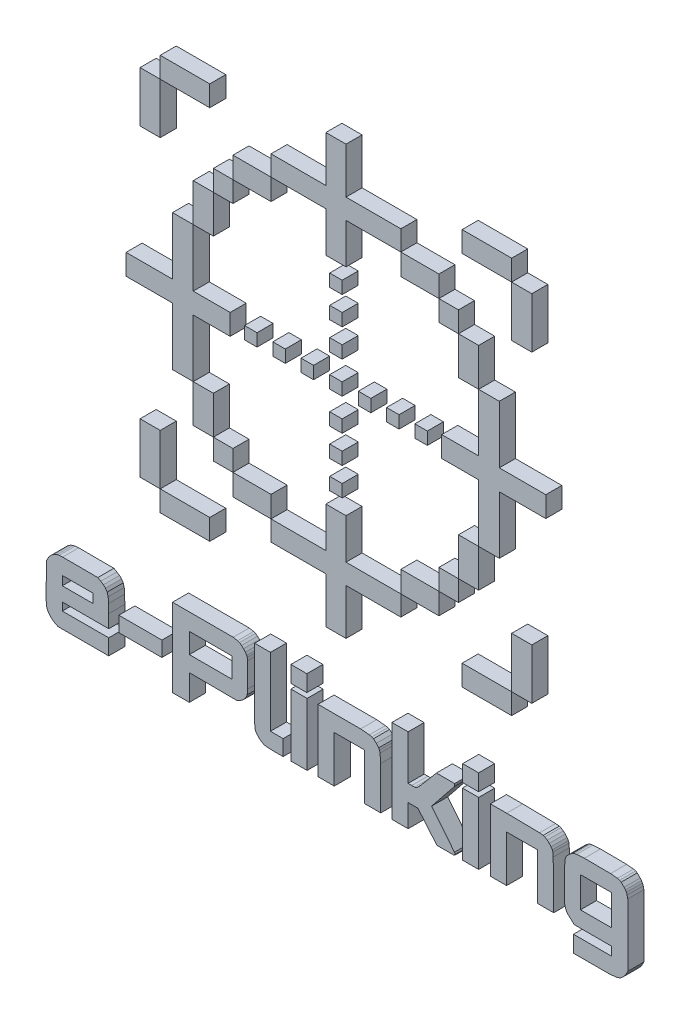
SolidWorks part; units mm, degrees
ref_plane "Plano frontal" through (0, 0, 0) normal (0, 0, 1) x (1, 0, 0)
ref_plane "Plano superior" through (0, 0, 0) normal (0, 1, 0) x (1, 0, 0)
ref_plane "Plano direito" through (0, 0, 0) normal (1, 0, 0) x (0, 0, -1)
sketch "Versão reduzida" plane through (0, 0, 0) normal (0, 0, 1) x (1, 0, 0)
  line L4 (5.1995, 6.5556) -> (5.7942, 6.5556)
  line L9 (5.1995, 6.5556) -> (5.1995, 6.307)
  line L10 (5.1995, 6.307) -> (5.7942, 6.307)
  line L11 (5.7942, 6.5556) -> (5.7942, 6.307)
  line L24 (0.9429, 4.1766) -> (6.3179, 4.1766) construction
  line L25 (5.7942, 6.307) -> (6.0362, 6.307)
  line L26 (5.7942, 6.307) -> (5.7942, 5.6987)
  line L28 (5.7942, 5.6987) -> (6.0362, 5.6987)
  line L29 (6.0362, 6.307) -> (6.0362, 5.6987)
  line L31 (3.805, 6.1961) -> (4.4636, 6.1961)
  line L33 (3.805, 5.9541) -> (4.4636, 5.9541)
  line L34 (4.4636, 6.1961) -> (4.4636, 5.9541)
  line L35 (4.4636, 5.9541) -> (4.9206, 5.9541)
  line L36 (4.4636, 5.9541) -> (4.4636, 5.6987)
  line L52 (4.4636, 5.6987) -> (4.9206, 5.6987)
  line L53 (4.9206, 5.9541) -> (4.9206, 5.6987)
  line L55 (4.9206, 5.6987) -> (5.1558, 5.6987)
  line L56 (4.9206, 5.6987) -> (4.9206, 5.4501)
  line L58 (4.9206, 5.4501) -> (5.1558, 5.4501)
  line L59 (5.1558, 5.6987) -> (5.1558, 5.4501)
  line L61 (5.1558, 5.4501) -> (5.3977, 5.4501)
  line L62 (5.1558, 5.4501) -> (5.1558, 4.9934)
  line L63 (5.1558, 4.9934) -> (5.3977, 4.9934)
  line L64 (5.3977, 5.4501) -> (5.3977, 4.9934)
  line L65 (5.3977, 4.9934) -> (5.6464, 4.9934)
  line L66 (5.3977, 4.9934) -> (5.3977, 4.3009)
  line L67 (5.6464, 4.9934) -> (5.6464, 4.3009)
  line L68 (4.9542, 4.3009) -> (5.3977, 4.3009)
  line L69 (4.9542, 4.3009) -> (4.9542, 4.0522)
  line L71 (6.2042, 4.3009) -> (6.2042, 4.0522)
  line L72 (3.805, 6.1961) -> (3.805, 6.7471)
  line L73 (3.805, 6.7471) -> (3.5631, 6.7471)
  line L82 (3.805, 5.9541) -> (3.805, 5.4703)
  line L85 (3.805, 5.4703) -> (3.5631, 5.4703)
  line L87 (4.2922, 4.2516) -> (4.4422, 4.2516)
  line L88 (4.6316, 4.2516) -> (4.7816, 4.2516)
  line L89 (3.805, 2.1571) -> (3.805, 1.606)
  line L90 (5.6464, 4.3009) -> (6.2042, 4.3009)
  line L91 (3.759, 5.309) -> (3.609, 5.309)
  line L92 (3.759, 5.309) -> (3.759, 5.159)
  line L105 (3.759, 5.159) -> (3.609, 5.159)
  line L106 (3.759, 4.9729) -> (3.609, 4.9729)
  line L107 (3.759, 4.9729) -> (3.759, 4.8229)
  line L108 (3.759, 4.8229) -> (3.609, 4.8229)
  line L125 (3.759, 4.6369) -> (3.609, 4.6369)
  line L126 (3.759, 4.6369) -> (3.759, 4.4869)
  line L127 (3.759, 4.4869) -> (3.609, 4.4869)
  line L128 (3.759, 4.2516) -> (3.609, 4.2516)
  line L141 (3.759, 4.2516) -> (3.759, 4.1016)
  line L142 (3.9529, 4.2516) -> (4.1029, 4.2516)
  line L143 (3.9529, 4.2516) -> (3.9529, 4.1016)
  line L160 (4.1029, 4.2516) -> (4.1029, 4.1016)
  line L161 (4.2922, 4.2516) -> (4.4422, 4.2516)
  line L166 (4.6316, 4.2516) -> (4.7816, 4.2516)
  line L169 (4.9542, 4.3009) -> (5.3977, 4.3009)
  line L173 (4.9542, 4.3009) -> (4.9542, 4.0522)
  line L177 (6.2042, 4.3009) -> (6.2042, 4.0522)
  line L183 (5.6464, 4.3009) -> (6.2042, 4.3009)
  line L184 (3.5631, 5.4703) -> (3.5631, 5.9541)
  line L185 (3.805, 5.4703) -> (3.5631, 5.4703)
  line L186 (3.805, 5.4703) -> (3.805, 5.9541)
  line L188 (3.805, 6.7471) -> (3.5631, 6.7471)
  line L189 (1.7217, 4.3009) -> (1.1639, 4.3009)
  line L191 (1.1639, 4.3009) -> (1.1639, 4.0522)
  line L192 (4.6316, 4.2516) -> (4.6316, 4.1016)
  line L193 (2.4139, 4.3009) -> (2.4139, 4.0522)
  line L206 (2.4139, 4.3009) -> (1.9703, 4.3009)
  line L207 (2.5865, 4.2516) -> (2.5865, 4.1016)
  line L208 (4.7816, 4.2516) -> (4.7816, 4.1016)
  line L209 (2.7365, 4.2516) -> (2.7365, 4.1016)
  line L219 (2.7365, 4.2516) -> (2.5865, 4.2516)
  line L220 (2.9258, 4.2516) -> (2.9258, 4.1016)
  line L347 (3.684, 3.7162) -> (3.684, 3.5302) construction
  line L409 (3.0758, 4.2516) -> (3.0758, 4.1016)
  line L410 (3.0758, 4.2516) -> (2.9258, 4.2516)
  line L411 (3.2652, 4.2516) -> (3.2652, 4.1016)
  line L412 (3.4152, 4.2516) -> (3.4152, 4.1016)
  line L413 (3.4152, 4.2516) -> (3.2652, 4.2516)
  line L414 (3.609, 4.2516) -> (3.609, 4.1016)
  line L415 (3.609, 4.6369) -> (3.609, 4.4869)
  line L416 (3.609, 4.9729) -> (3.609, 4.8229)
  line L417 (3.609, 5.309) -> (3.609, 5.159)
  line L418 (1.7217, 4.3009) -> (1.1639, 4.3009)
  line L419 (2.7365, 4.2516) -> (2.5865, 4.2516)
  line L420 (3.0758, 4.2516) -> (2.9258, 4.2516)
  line L421 (3.5631, 5.9541) -> (3.5631, 5.4703)
  line L422 (3.5631, 6.1961) -> (3.5631, 6.7471)
  line L423 (1.1639, 4.3009) -> (1.1639, 4.0522)
  line L424 (2.4139, 4.3009) -> (2.4139, 4.0522)
  line L425 (2.4139, 4.3009) -> (1.9703, 4.3009)
  line L426 (1.7217, 4.9934) -> (1.7217, 4.3009)
  line L427 (1.9703, 4.9934) -> (1.9703, 4.3009)
  line L428 (1.9703, 4.9934) -> (1.7217, 4.9934)
  line L429 (1.9703, 5.4501) -> (1.9703, 4.9934)
  line L430 (2.2123, 4.9934) -> (1.9703, 4.9934)
  line L431 (2.2123, 5.4501) -> (2.2123, 4.9934)
  line L432 (2.2123, 5.4501) -> (1.9703, 5.4501)
  line L433 (2.2123, 5.6987) -> (2.2123, 5.4501)
  line L434 (2.4475, 5.4501) -> (2.2123, 5.4501)
  line L435 (2.4475, 5.6987) -> (2.4475, 5.4501)
  line L436 (2.4475, 5.6987) -> (2.2123, 5.6987)
  line L437 (2.4475, 5.9541) -> (2.4475, 5.6987)
  line L438 (2.9045, 5.6987) -> (2.4475, 5.6987)
  line L439 (2.9045, 5.9541) -> (2.9045, 5.6987)
  line L440 (2.9045, 5.9541) -> (2.4475, 5.9541)
  line L441 (2.9045, 6.1961) -> (2.9045, 5.9541)
  line L442 (3.5631, 5.9541) -> (2.9045, 5.9541)
  line L443 (3.684, 1.606) -> (3.684, 1.4107) construction
  line L444 (3.5631, 6.1961) -> (2.9045, 6.1961)
  line L445 (1.3319, 6.307) -> (1.3319, 5.6987)
  line L446 (1.5738, 5.6987) -> (1.3319, 5.6987)
  line L447 (1.5738, 6.307) -> (1.5738, 5.6987)
  line L448 (1.5738, 6.307) -> (1.3319, 6.307)
  line L449 (1.5738, 6.5556) -> (1.5738, 6.307)
  line L450 (2.1686, 6.307) -> (1.5738, 6.307)
  line L451 (2.1686, 6.5556) -> (2.1686, 6.307)
  line L452 (2.1686, 6.5556) -> (1.5738, 6.5556)
  line L453 (2.1686, 1.7975) -> (1.5738, 1.7975)
  line L454 (2.1686, 1.7975) -> (2.1686, 2.0462)
  line L455 (2.1686, 2.0462) -> (1.5738, 2.0462)
  line L456 (1.5738, 1.7975) -> (1.5738, 2.0462)
  line L457 (1.5738, 2.0462) -> (1.3319, 2.0462)
  line L458 (1.5738, 2.0462) -> (1.5738, 2.6544)
  line L459 (1.5738, 2.6544) -> (1.3319, 2.6544)
  line L460 (1.3319, 2.0462) -> (1.3319, 2.6544)
  line L461 (3.5631, 2.1571) -> (2.9045, 2.1571)
  line L462 (3.684, 5.159) -> (3.684, 4.9729) construction
  line L463 (3.5631, 2.399) -> (2.9045, 2.399)
  line L464 (2.9045, 2.1571) -> (2.9045, 2.399)
  line L465 (2.9045, 2.399) -> (2.4475, 2.399)
  line L466 (2.9045, 2.399) -> (2.9045, 2.6544)
  line L467 (2.9045, 2.6544) -> (2.4475, 2.6544)
  line L468 (2.4475, 2.399) -> (2.4475, 2.6544)
  line L469 (2.4475, 2.6544) -> (2.2123, 2.6544)
  line L470 (2.4475, 2.6544) -> (2.4475, 2.9031)
  line L471 (2.4475, 2.9031) -> (2.2123, 2.9031)
  line L472 (2.2123, 2.6544) -> (2.2123, 2.9031)
  line L473 (2.2123, 2.9031) -> (1.9703, 2.9031)
  line L474 (2.2123, 2.9031) -> (2.2123, 3.3597)
  line L475 (2.2123, 3.3597) -> (1.9703, 3.3597)
  line L476 (1.9703, 2.9031) -> (1.9703, 3.3597)
  line L477 (1.9703, 3.3597) -> (1.7217, 3.3597)
  line L478 (1.9703, 3.3597) -> (1.9703, 4.0522)
  line L479 (1.7217, 3.3597) -> (1.7217, 4.0522)
  line L480 (2.4139, 4.0522) -> (1.9703, 4.0522)
  line L481 (3.5631, 2.1571) -> (3.5631, 1.606)
  line L482 (3.5631, 2.399) -> (3.5631, 2.8829)
  line L483 (3.0758, 4.1016) -> (2.9258, 4.1016)
  line L484 (2.7365, 4.1016) -> (2.5865, 4.1016)
  line L485 (1.7217, 4.0522) -> (1.1639, 4.0522)
  line L486 (3.609, 3.0442) -> (3.609, 3.1942)
  line L487 (3.609, 3.3802) -> (3.609, 3.5302)
  line L488 (3.609, 3.7162) -> (3.609, 3.8662)
  line L489 (3.4152, 4.1016) -> (3.2652, 4.1016)
  line L490 (3.0758, 4.1016) -> (2.9258, 4.1016)
  line L491 (2.7365, 4.1016) -> (2.5865, 4.1016)
  line L492 (2.4139, 4.0522) -> (1.9703, 4.0522)
  line L493 (1.7217, 4.0522) -> (1.1639, 4.0522)
  line L494 (3.5631, 2.1571) -> (3.5631, 1.606)
  line L495 (3.805, 1.606) -> (3.5631, 1.606)
  line L496 (3.805, 2.8829) -> (3.805, 2.399)
  line L497 (3.805, 2.8829) -> (3.5631, 2.8829)
  line L498 (3.5631, 2.8829) -> (3.5631, 2.399)
  line L499 (5.6464, 4.0522) -> (6.2042, 4.0522)
  line L500 (4.9542, 4.0522) -> (5.3977, 4.0522)
  line L501 (4.6316, 4.1016) -> (4.7816, 4.1016)
  line L502 (4.2922, 4.1016) -> (4.4422, 4.1016)
  line L503 (3.9529, 4.1016) -> (4.1029, 4.1016)
  line L504 (3.759, 4.1016) -> (3.609, 4.1016)
  line L505 (3.684, 3.3802) -> (3.684, 3.1942) construction
  line L506 (3.759, 3.8662) -> (3.609, 3.8662)
  line L507 (3.759, 3.7162) -> (3.759, 3.8662)
  line L508 (3.759, 3.7162) -> (3.609, 3.7162)
  line L509 (3.684, 3.0442) -> (3.684, 2.8829) construction
  line L510 (3.759, 3.5302) -> (3.609, 3.5302)
  line L511 (3.759, 3.3802) -> (3.759, 3.5302)
  line L512 (3.759, 3.3802) -> (3.609, 3.3802)
  line L513 (4.2922, 4.2516) -> (4.2922, 4.1016)
  line L514 (3.759, 3.1942) -> (3.609, 3.1942)
  line L515 (3.759, 3.0442) -> (3.759, 3.1942)
  line L516 (3.759, 3.0442) -> (3.609, 3.0442)
  line L517 (5.6464, 4.0522) -> (6.2042, 4.0522)
  line L518 (4.6316, 4.1016) -> (4.7816, 4.1016)
  line L519 (4.2922, 4.1016) -> (4.4422, 4.1016)
  line L520 (3.805, 2.8829) -> (3.5631, 2.8829)
  line L521 (3.805, 2.399) -> (3.805, 2.8829)
  line L522 (3.684, 4.8229) -> (3.684, 4.6369) construction
  line L523 (3.805, 1.606) -> (3.5631, 1.606)
  line L524 (3.805, 2.1571) -> (3.805, 1.606)
  line L525 (3.684, 4.4869) -> (3.684, 4.2516) construction
  line L526 (4.9542, 4.0522) -> (5.3977, 4.0522)
  line L527 (5.6464, 3.3597) -> (5.6464, 4.0522)
  line L528 (5.3977, 3.3597) -> (5.3977, 4.0522)
  line L529 (5.3977, 3.3597) -> (5.6464, 3.3597)
  line L530 (5.3977, 2.9031) -> (5.3977, 3.3597)
  line L531 (5.1558, 3.3597) -> (5.3977, 3.3597)
  line L532 (5.1558, 2.9031) -> (5.1558, 3.3597)
  line L533 (5.1558, 2.9031) -> (5.3977, 2.9031)
  line L534 (5.1558, 2.6544) -> (5.1558, 2.9031)
  line L535 (4.9206, 2.9031) -> (5.1558, 2.9031)
  line L536 (4.9206, 2.6544) -> (4.9206, 2.9031)
  line L537 (4.9206, 2.6544) -> (5.1558, 2.6544)
  line L538 (4.9206, 2.399) -> (4.9206, 2.6544)
  line L539 (4.4636, 2.6544) -> (4.9206, 2.6544)
  line L540 (4.4636, 2.399) -> (4.4636, 2.6544)
  line L541 (4.4636, 2.399) -> (4.9206, 2.399)
  line L542 (4.4636, 2.1571) -> (4.4636, 2.399)
  line L543 (3.805, 2.399) -> (4.4636, 2.399)
  line L544 (3.684, 4.1016) -> (3.684, 3.8662) construction
  line L545 (3.805, 2.1571) -> (4.4636, 2.1571)
  line L546 (6.0362, 2.0462) -> (6.0362, 2.6544)
  line L547 (5.7942, 2.6544) -> (6.0362, 2.6544)
  line L548 (5.7942, 2.0462) -> (5.7942, 2.6544)
  line L549 (5.7942, 2.0462) -> (6.0362, 2.0462)
  line L550 (5.7942, 1.7975) -> (5.7942, 2.0462)
  line L551 (5.1995, 2.0462) -> (5.7942, 2.0462)
  line L552 (5.1995, 1.7975) -> (5.1995, 2.0462)
  line L553 (5.1995, 1.7975) -> (5.7942, 1.7975)
  line L554 (3.5631, 6.1961) -> (3.5631, 6.7471)
  line L555 (3.684, 5.4703) -> (3.684, 5.309) construction
  line L556 (4.4422, 4.2516) -> (4.4422, 4.1016)
  line L557 (3.805, 6.1961) -> (3.805, 6.7471)
  line L558 (0.4024, 0.7509) -> (0.8245, 0.7492)
  line L559 (0.8245, 0.7492) -> (0.8605, 0.7292)
  line L560 (0.8605, 0.7292) -> (0.8917, 0.7082)
  line L561 (0.8917, 0.7082) -> (0.9161, 0.6856)
  line L562 (0.9161, 0.6856) -> (0.9368, 0.6539)
  line L563 (0.9368, 0.6539) -> (0.9487, 0.6117)
  line L564 (0.9487, 0.6117) -> (0.9542, 0.5447)
  line L565 (0.9542, 0.5447) -> (0.9555, 0.4388)
  line L566 (0.9555, 0.4388) -> (0.9555, 0.2821)
  line L567 (0.9555, 0.2821) -> (0.3978, 0.2821)
  line L568 (0.3978, 0.2821) -> (0.3978, 0.1872)
  line L569 (0.3978, 0.1872) -> (0.9555, 0.188)
  line L570 (0.9555, 0.188) -> (0.9555, -0.0002)
  line L571 (0.9555, -0.0002) -> (0.3473, 0)
  line L572 (0.3473, 0) -> (0.3135, 0.0157)
  line L573 (0.3135, 0.0157) -> (0.2806, 0.0362)
  line L574 (0.2806, 0.0362) -> (0.2511, 0.0644)
  line L575 (0.2511, 0.0644) -> (0.2275, 0.0972)
  line L576 (0.2275, 0.0972) -> (0.2124, 0.1318)
  line L577 (0.2124, 0.1318) -> (0.2072, 0.1586)
  line L578 (0.2072, 0.1586) -> (0.2044, 0.2027)
  line L579 (0.2044, 0.2027) -> (0.2062, 0.6148)
  line L580 (0.2062, 0.6148) -> (0.2244, 0.6493)
  line L581 (0.2244, 0.6493) -> (0.2449, 0.6804)
  line L582 (0.2449, 0.6804) -> (0.2706, 0.7069)
  line L583 (0.2706, 0.7069) -> (0.3004, 0.7277)
  line L584 (0.3004, 0.7277) -> (0.3346, 0.7423)
  line L585 (0.3346, 0.7423) -> (0.3597, 0.7478)
  line L586 (0.3597, 0.7478) -> (0.4024, 0.7509)
  line L587 (1.7217, 0.0002) -> (1.7217, 0.9411)
  line L588 (0.3978, 0.5576) -> (0.7674, 0.5576)
  line L589 (0.3978, 0.5576) -> (0.3978, 0.4501)
  line L590 (0.3978, 0.4501) -> (0.7674, 0.4501)
  line L591 (0.7674, 0.5576) -> (0.7674, 0.4501)
  line L592 (1.0765, 0.4837) -> (1.594, 0.4837)
  line L593 (1.0765, 0.4837) -> (1.0765, 0.3023)
  line L594 (1.0765, 0.3023) -> (1.594, 0.3023)
  line L595 (1.594, 0.4837) -> (1.594, 0.3023)
  line L596 (1.9233, 0.7391) -> (2.434, 0.7391)
  line L597 (1.9233, 0.7391) -> (1.9233, 0.4971)
  line L598 (1.9233, 0.4971) -> (2.434, 0.4971)
  line L599 (2.434, 0.7391) -> (2.434, 0.4971)
  line L600 (3.143, 1.0045) -> (3.3349, 1.0045)
  line L601 (3.143, 1.0045) -> (3.143, 0.8075)
  line L602 (3.143, 0.8075) -> (3.3349, 0.8075)
  line L603 (3.3349, 1.0045) -> (3.3349, 0.8075)
  line L604 (5.2062, 1.0045) -> (5.3977, 1.0045)
  line L605 (5.2062, 1.0045) -> (5.2062, 0.8075)
  line L606 (5.2062, 0.8075) -> (5.3977, 0.8075)
  line L607 (5.3977, 1.0045) -> (5.3977, 0.8075)
  line L608 (6.6209, 0.5576) -> (6.9938, 0.5576)
  line L609 (6.6209, 0.5576) -> (6.6209, 0.1914)
  line L610 (6.6209, 0.1914) -> (6.9938, 0.1914)
  line L611 (6.9938, 0.5576) -> (6.9938, 0.1914)
  line L612 (1.7217, 0.9411) -> (2.4504, 0.9411)
  line L613 (2.4504, 0.9411) -> (2.5026, 0.9311)
  line L614 (2.5026, 0.9311) -> (2.5248, 0.9228)
  line L615 (2.5248, 0.9228) -> (2.5496, 0.9061)
  line L616 (2.5496, 0.9061) -> (2.5743, 0.8838)
  line L617 (2.5743, 0.8838) -> (2.5964, 0.8586)
  line L618 (2.5964, 0.8586) -> (2.6131, 0.8332)
  line L619 (2.6131, 0.8332) -> (2.6198, 0.8152)
  line L620 (2.6198, 0.8152) -> (2.6238, 0.7845)
  line L621 (2.6238, 0.7845) -> (2.6218, 0.4873)
  line L622 (2.6218, 0.4873) -> (2.6186, 0.4266)
  line L623 (2.6186, 0.4266) -> (2.6055, 0.3949)
  line L624 (2.6055, 0.3949) -> (2.5876, 0.3682)
  line L625 (2.5876, 0.3682) -> (2.564, 0.3454)
  line L626 (2.564, 0.3454) -> (2.5339, 0.3255)
  line L627 (2.5339, 0.3255) -> (2.4979, 0.3056)
  line L628 (2.4979, 0.3056) -> (1.9233, 0.3095)
  line L629 (1.9233, 0.3095) -> (1.9233, 0.0002)
  line L630 (1.9233, 0.0002) -> (1.7217, 0.0002)
  line L631 (2.7082, 1.0079) -> (2.8977, 1.0079)
  line L632 (2.8977, 1.0079) -> (2.8977, 0.1869)
  line L633 (2.8977, 0.1869) -> (3.0504, 0.1871)
  line L634 (3.0504, 0.1871) -> (3.0504, -0.0002)
  line L635 (3.0504, -0.0002) -> (2.9204, -0.0003)
  line L636 (2.9204, -0.0003) -> (2.8557, 0.0024)
  line L637 (2.8557, 0.0024) -> (2.8317, 0.0062)
  line L638 (2.8317, 0.0062) -> (2.8137, 0.0125)
  line L639 (2.8137, 0.0125) -> (2.786, 0.0281)
  line L640 (2.786, 0.0281) -> (2.7602, 0.0485)
  line L641 (2.7602, 0.0485) -> (2.738, 0.0719)
  line L642 (2.738, 0.0719) -> (2.7213, 0.0966)
  line L643 (2.7213, 0.0966) -> (2.7128, 0.1197)
  line L644 (2.7128, 0.1197) -> (2.7082, 0.1766)
  line L645 (2.7082, 0.1766) -> (2.7082, 1.0079)
  line L646 (3.6639, 0.5576) -> (4.0268, 0.5576)
  line L647 (3.143, 0.7492) -> (3.3379, 0.7492)
  line L648 (3.143, 0.7492) -> (3.143, -0.0002)
  line L649 (3.143, -0.0002) -> (3.3379, -0.0002)
  line L650 (3.3379, 0.7492) -> (3.3379, -0.0002)
  line L651 (3.469, 0.753) -> (3.6639, 0.753)
  line L652 (3.469, 0.753) -> (3.469, -0.0002)
  line L653 (3.469, -0.0002) -> (3.6639, -0.0002)
  line L654 (3.6639, 0.5576) -> (3.6639, -0.0002)
  line L655 (4.0268, 0.5576) -> (4.0268, -0.0002)
  line L656 (4.0268, -0.0002) -> (4.2222, -0.0002)
  line L657 (4.2222, -0.0002) -> (4.2222, 0.5147)
  line L658 (4.2222, 0.5147) -> (4.2132, 0.618)
  line L659 (4.2132, 0.618) -> (4.2073, 0.6461)
  line L660 (4.2073, 0.6461) -> (4.1985, 0.6653)
  line L661 (4.1985, 0.6653) -> (4.169, 0.6977)
  line L662 (4.169, 0.6977) -> (4.1349, 0.7281)
  line L663 (4.1349, 0.7281) -> (4.1145, 0.7373)
  line L664 (4.1145, 0.7373) -> (4.0853, 0.7434)
  line L665 (4.0853, 0.7434) -> (3.9803, 0.753)
  line L666 (3.9803, 0.753) -> (3.6639, 0.753)
  line L667 (4.551, 0.4717) -> (4.595, 0.4717)
  line L668 (4.3561, 1.0079) -> (4.551, 1.0079)
  line L669 (4.3561, 1.0079) -> (4.3561, -0.0002)
  line L670 (4.3561, -0.0002) -> (4.551, -0.0002)
  line L671 (4.551, 1.0079) -> (4.551, 0.4717)
  line L672 (4.595, 0.4717) -> (4.6283, 0.472)
  line L673 (4.6283, 0.472) -> (4.6514, 0.4755)
  line L674 (4.6514, 0.4755) -> (4.6954, 0.519)
  line L675 (4.6954, 0.519) -> (4.8906, 0.7492)
  line L676 (4.8906, 0.7492) -> (5.1099, 0.7492)
  line L677 (5.1099, 0.7492) -> (5.1088, 0.7321)
  line L678 (5.1088, 0.7321) -> (5.1045, 0.7143)
  line L679 (5.1045, 0.7143) -> (4.8332, 0.3763)
  line L680 (4.8332, 0.3763) -> (5.1076, 0.0337)
  line L681 (5.1076, 0.0337) -> (5.1154, 0.015)
  line L682 (5.1154, 0.015) -> (5.1137, 0.0062)
  line L683 (0, 0) -> (7.4151, 0) construction
  line L684 (5.1137, 0.0062) -> (5.1008, 0)
  line L685 (6.9938, 0) -> (6.9938, -0.1043)
  line L686 (5.1008, 0) -> (4.8971, -0.0001)
  line L687 (4.8971, -0.0001) -> (4.6684, 0.272)
  line L688 (4.6684, 0.272) -> (4.551, 0.272)
  line L689 (4.551, 0.272) -> (4.551, -0.0002)
  line L690 (5.7338, 0.753) -> (6.1303, 0.7475)
  line L691 (5.2027, 0.7492) -> (5.398, 0.7492)
  line L692 (5.2027, 0.7492) -> (5.2027, -0.0002)
  line L693 (5.2027, -0.0002) -> (5.398, -0.0002)
  line L694 (5.398, 0.7492) -> (5.398, -0.0002)
  line L695 (5.5389, 0.753) -> (5.7338, 0.753)
  line L696 (5.5389, 0.753) -> (5.5389, -0.0002)
  line L697 (5.5389, -0.0002) -> (5.7338, -0.0002)
  line L698 (5.7338, 0.5576) -> (5.7338, -0.0002)
  line L699 (6.1303, 0.7475) -> (6.1739, 0.7428)
  line L700 (6.1739, 0.7428) -> (6.1923, 0.7354)
  line L701 (6.1923, 0.7354) -> (6.2214, 0.7172)
  line L702 (6.2214, 0.7172) -> (6.2459, 0.6956)
  line L703 (6.2459, 0.6956) -> (6.267, 0.6712)
  line L704 (6.267, 0.6712) -> (6.2826, 0.6462)
  line L705 (6.2826, 0.6462) -> (6.2894, 0.6243)
  line L706 (6.2894, 0.6243) -> (6.2933, 0.5769)
  line L707 (6.2933, 0.5769) -> (6.2989, -0.0002)
  line L708 (6.2989, -0.0002) -> (6.1034, -0.0002)
  line L709 (6.1034, -0.0002) -> (6.1034, 0.5576)
  line L710 (6.1034, 0.5576) -> (5.7338, 0.5576)
  line L711 (6.9938, -0.1043) -> (6.5369, -0.1043)
  line L712 (6.5369, -0.1043) -> (6.5369, -0.3019)
  line L713 (6.5369, -0.3019) -> (6.9623, -0.3019)
  line L714 (6.9623, -0.3019) -> (7.0512, -0.2937)
  line L715 (7.0512, -0.2937) -> (7.0964, -0.2797)
  line L716 (7.0964, -0.2797) -> (7.1302, -0.2526)
  line L717 (7.1302, -0.2526) -> (7.1539, -0.2261)
  line L718 (7.1539, -0.2261) -> (7.173, -0.1965)
  line L719 (7.173, -0.1965) -> (7.1887, -0.1648)
  line L720 (7.1887, -0.1648) -> (7.1887, 0.5892)
  line L721 (7.1887, 0.5892) -> (7.1811, 0.6245)
  line L722 (7.1811, 0.6245) -> (7.1725, 0.6497)
  line L723 (7.1725, 0.6497) -> (7.1605, 0.6689)
  line L724 (7.1605, 0.6689) -> (7.1444, 0.6879)
  line L725 (7.1444, 0.6879) -> (7.1094, 0.7235)
  line L726 (7.1094, 0.7235) -> (7.0904, 0.7345)
  line L727 (7.0904, 0.7345) -> (7.0654, 0.7419)
  line L728 (7.0654, 0.7419) -> (6.9816, 0.749)
  line L729 (6.9816, 0.749) -> (6.6672, 0.7514)
  line L730 (6.6672, 0.7514) -> (6.5757, 0.7461)
  line L731 (6.5757, 0.7461) -> (6.547, 0.7402)
  line L732 (6.547, 0.7402) -> (6.5251, 0.7314)
  line L733 (6.5251, 0.7314) -> (6.4882, 0.7035)
  line L734 (6.4882, 0.7035) -> (6.4547, 0.6683)
  line L735 (6.4547, 0.6683) -> (6.4443, 0.6489)
  line L736 (6.4443, 0.6489) -> (6.437, 0.6238)
  line L737 (6.437, 0.6238) -> (6.4296, 0.5428)
  line L738 (6.4296, 0.5428) -> (6.4271, 0.3981)
  line L739 (6.4271, 0.3981) -> (6.4274, 0.2263)
  line L740 (6.4274, 0.2263) -> (6.4327, 0.1445)
  line L741 (6.4327, 0.1445) -> (6.4442, 0.1086)
  line L742 (6.4442, 0.1086) -> (6.4628, 0.0752)
  line L743 (6.4628, 0.0752) -> (6.5471, 0)
  line L744 (6.5471, 0) -> (6.9938, 0)
  point P169 (3.684, 4.1766)
  point P369 (0, 0)
  point P370 (0, 0)
sketch "Frame 190 x 150" plane through (0, 0, 0) normal (0, 0, 1) x (1, 0, 0)
  line L4 (31.5113, 69.6228) -> (43.847, 69.6228)
  line L9 (31.5113, 69.6228) -> (31.5113, 64.4659)
  line L10 (31.5113, 64.4659) -> (43.847, 64.4659)
  line L11 (43.847, 69.6228) -> (43.847, 64.4659)
  line L24 (-56.7725, 20.2803) -> (54.7079, 20.2803) construction
  line L25 (43.847, 64.4659) -> (48.8648, 64.4659)
  line L26 (43.847, 64.4659) -> (43.847, 51.8512)
  line L28 (43.847, 51.8512) -> (48.8648, 51.8512)
  line L29 (48.8648, 64.4659) -> (48.8648, 51.8512)
  line L31 (2.589, 62.1656) -> (16.2488, 62.1656)
  line L33 (2.589, 57.1478) -> (16.2488, 57.1478)
  line L34 (16.2488, 62.1656) -> (16.2488, 57.1478)
  line L35 (16.2488, 57.1478) -> (25.7271, 57.1478)
  line L36 (16.2488, 57.1478) -> (16.2488, 51.8512)
  line L52 (16.2488, 51.8512) -> (25.7271, 51.8512)
  line L53 (25.7271, 57.1478) -> (25.7271, 51.8512)
  line L55 (25.7271, 51.8512) -> (30.6056, 51.8512)
  line L56 (25.7271, 51.8512) -> (25.7271, 46.6939)
  line L58 (25.7271, 46.6939) -> (30.6056, 46.6939)
  line L59 (30.6056, 51.8512) -> (30.6056, 46.6939)
  line L61 (30.6056, 46.6939) -> (35.6234, 46.6939)
  line L62 (30.6056, 46.6939) -> (30.6056, 37.2219)
  line L63 (30.6056, 37.2219) -> (35.6234, 37.2219)
  line L64 (35.6234, 46.6939) -> (35.6234, 37.2219)
  line L65 (35.6234, 37.2219) -> (40.7807, 37.2219)
  line L66 (35.6234, 37.2219) -> (35.6234, 22.8589)
  line L67 (40.7807, 37.2219) -> (40.7807, 22.8589)
  line L68 (26.4242, 22.8589) -> (35.6234, 22.8589)
  line L69 (26.4242, 22.8589) -> (26.4242, 17.7017)
  line L71 (52.3497, 22.8589) -> (52.3497, 17.7017)
  line L72 (2.589, 62.1656) -> (2.589, 73.5953)
  line L73 (2.589, 73.5953) -> (-2.4289, 73.5953)
  line L82 (2.589, 57.1478) -> (2.589, 47.1121)
  line L85 (2.589, 47.1121) -> (-2.4289, 47.1121)
  line L87 (12.6945, 21.8358) -> (15.8056, 21.8358)
  line L88 (19.7335, 21.8358) -> (22.8446, 21.8358)
  line L89 (2.589, -21.605) -> (2.589, -33.0347)
  line L90 (40.7807, 22.8589) -> (52.3497, 22.8589)
  line L91 (1.6356, 43.7668) -> (-1.4755, 43.7668)
  line L92 (1.6356, 43.7668) -> (1.6356, 40.6557)
  line L105 (1.6356, 40.6557) -> (-1.4755, 40.6557)
  line L106 (1.6356, 36.7975) -> (-1.4755, 36.7975)
  line L107 (1.6356, 36.7975) -> (1.6356, 33.6864)
  line L108 (1.6356, 33.6864) -> (-1.4755, 33.6864)
  line L125 (1.6356, 29.8282) -> (-1.4755, 29.8282)
  line L126 (1.6356, 29.8282) -> (1.6356, 26.7171)
  line L127 (1.6356, 26.7171) -> (-1.4755, 26.7171)
  line L128 (1.6356, 21.8358) -> (-1.4755, 21.8358)
  line L141 (1.6356, 21.8358) -> (1.6356, 18.7247)
  line L142 (5.6555, 21.8358) -> (8.7666, 21.8358)
  line L143 (5.6555, 21.8358) -> (5.6555, 18.7247)
  line L160 (8.7666, 21.8358) -> (8.7666, 18.7247)
  line L161 (12.6945, 21.8358) -> (15.8056, 21.8358)
  line L166 (19.7335, 21.8358) -> (22.8446, 21.8358)
  line L169 (26.4242, 22.8589) -> (35.6234, 22.8589)
  line L173 (26.4242, 22.8589) -> (26.4242, 17.7017)
  line L177 (52.3497, 22.8589) -> (52.3497, 17.7017)
  line L183 (40.7807, 22.8589) -> (52.3497, 22.8589)
  line L184 (-2.4289, 47.1121) -> (-2.4289, 57.1478)
  line L185 (2.589, 47.1121) -> (-2.4289, 47.1121)
  line L186 (2.589, 47.1121) -> (2.589, 57.1478)
  line L188 (2.589, 73.5953) -> (-2.4289, 73.5953)
  line L189 (-40.6206, 22.8589) -> (-52.1896, 22.8589)
  line L191 (-52.1896, 22.8589) -> (-52.1896, 17.7017)
  line L192 (19.7335, 21.8358) -> (19.7335, 18.7247)
  line L193 (-26.2641, 22.8589) -> (-26.2641, 17.7017)
  line L206 (-26.2641, 22.8589) -> (-35.4633, 22.8589)
  line L207 (-22.6844, 21.8358) -> (-22.6844, 18.7247)
  line L208 (22.8446, 21.8358) -> (22.8446, 18.7247)
  line L209 (-19.5733, 21.8358) -> (-19.5733, 18.7247)
  line L219 (-19.5733, 21.8358) -> (-22.6844, 21.8358)
  line L220 (-15.6455, 21.8358) -> (-15.6455, 18.7247)
  line L347 (0.0801, 10.7324) -> (0.0801, 6.8742) construction
  line L409 (-12.5344, 21.8358) -> (-12.5344, 18.7247)
  line L410 (-12.5344, 21.8358) -> (-15.6455, 21.8358)
  line L411 (-8.6065, 21.8358) -> (-8.6065, 18.7247)
  line L412 (-5.4954, 21.8358) -> (-5.4954, 18.7247)
  line L413 (-5.4954, 21.8358) -> (-8.6065, 21.8358)
  line L414 (-1.4755, 21.8358) -> (-1.4755, 18.7247)
  line L415 (-1.4755, 29.8282) -> (-1.4755, 26.7171)
  line L416 (-1.4755, 36.7975) -> (-1.4755, 33.6864)
  line L417 (-1.4755, 43.7668) -> (-1.4755, 40.6557)
  line L418 (-40.6206, 22.8589) -> (-52.1896, 22.8589)
  line L419 (-19.5733, 21.8358) -> (-22.6844, 21.8358)
  line L420 (-12.5344, 21.8358) -> (-15.6455, 21.8358)
  line L421 (-2.4289, 57.1478) -> (-2.4289, 47.1121)
  line L422 (-2.4289, 62.1656) -> (-2.4289, 73.5953)
  line L423 (-52.1896, 22.8589) -> (-52.1896, 17.7017)
  line L424 (-26.2641, 22.8589) -> (-26.2641, 17.7017)
  line L425 (-26.2641, 22.8589) -> (-35.4633, 22.8589)
  line L426 (-40.6206, 37.2219) -> (-40.6206, 22.8589)
  line L427 (-35.4633, 37.2219) -> (-35.4633, 22.8589)
  line L428 (-35.4633, 37.2219) -> (-40.6206, 37.2219)
  line L429 (-35.4633, 46.6939) -> (-35.4633, 37.2219)
  line L430 (-30.4454, 37.2219) -> (-35.4633, 37.2219)
  line L431 (-30.4454, 46.6939) -> (-30.4454, 37.2219)
  line L432 (-30.4454, 46.6939) -> (-35.4633, 46.6939)
  line L433 (-30.4454, 51.8512) -> (-30.4454, 46.6939)
  line L434 (-25.5669, 46.6939) -> (-30.4454, 46.6939)
  line L435 (-25.5669, 51.8512) -> (-25.5669, 46.6939)
  line L436 (-25.5669, 51.8512) -> (-30.4454, 51.8512)
  line L437 (-25.5669, 57.1478) -> (-25.5669, 51.8512)
  line L438 (-16.0887, 51.8512) -> (-25.5669, 51.8512)
  line L439 (-16.0887, 57.1478) -> (-16.0887, 51.8512)
  line L440 (-16.0887, 57.1478) -> (-25.5669, 57.1478)
  line L441 (-16.0887, 62.1656) -> (-16.0887, 57.1478)
  line L442 (-2.4289, 57.1478) -> (-16.0887, 57.1478)
  line L443 (0.0801, -33.0347) -> (0.0801, -37.0859) construction
  line L444 (-2.4289, 62.1656) -> (-16.0887, 62.1656)
  line L445 (-48.7047, 64.4659) -> (-48.7047, 51.8512)
  line L446 (-43.6868, 51.8512) -> (-48.7047, 51.8512)
  line L447 (-43.6868, 64.4659) -> (-43.6868, 51.8512)
  line L448 (-43.6868, 64.4659) -> (-48.7047, 64.4659)
  line L449 (-43.6868, 69.6228) -> (-43.6868, 64.4659)
  line L450 (-31.3512, 64.4659) -> (-43.6868, 64.4659)
  line L451 (-31.3512, 69.6228) -> (-31.3512, 64.4659)
  line L452 (-31.3512, 69.6228) -> (-43.6868, 69.6228)
  line L453 (-31.3512, -29.0622) -> (-43.6868, -29.0622)
  line L454 (-31.3512, -29.0622) -> (-31.3512, -23.9054)
  line L455 (-31.3512, -23.9054) -> (-43.6868, -23.9054)
  line L456 (-43.6868, -29.0622) -> (-43.6868, -23.9054)
  line L457 (-43.6868, -23.9054) -> (-48.7047, -23.9054)
  line L458 (-43.6868, -23.9054) -> (-43.6868, -11.2906)
  line L459 (-43.6868, -11.2906) -> (-48.7047, -11.2906)
  line L460 (-48.7047, -23.9054) -> (-48.7047, -11.2906)
  line L461 (-2.4289, -21.605) -> (-16.0887, -21.605)
  line L462 (0.0801, 40.6557) -> (0.0801, 36.7975) construction
  line L463 (-2.4289, -16.5872) -> (-16.0887, -16.5872)
  line L464 (-16.0887, -21.605) -> (-16.0887, -16.5872)
  line L465 (-16.0887, -16.5872) -> (-25.5669, -16.5872)
  line L466 (-16.0887, -16.5872) -> (-16.0887, -11.2906)
  line L467 (-16.0887, -11.2906) -> (-25.5669, -11.2906)
  line L468 (-25.5669, -16.5872) -> (-25.5669, -11.2906)
  line L469 (-25.5669, -11.2906) -> (-30.4454, -11.2906)
  line L470 (-25.5669, -11.2906) -> (-25.5669, -6.1333)
  line L471 (-25.5669, -6.1333) -> (-30.4454, -6.1333)
  line L472 (-30.4454, -11.2906) -> (-30.4454, -6.1333)
  line L473 (-30.4454, -6.1333) -> (-35.4633, -6.1333)
  line L474 (-30.4454, -6.1333) -> (-30.4454, 3.3386)
  line L475 (-30.4454, 3.3386) -> (-35.4633, 3.3386)
  line L476 (-35.4633, -6.1333) -> (-35.4633, 3.3386)
  line L477 (-35.4633, 3.3386) -> (-40.6206, 3.3386)
  line L478 (-35.4633, 3.3386) -> (-35.4633, 17.7017)
  line L479 (-40.6206, 3.3386) -> (-40.6206, 17.7017)
  line L480 (-26.2641, 17.7017) -> (-35.4633, 17.7017)
  line L481 (-2.4289, -21.605) -> (-2.4289, -33.0347)
  line L482 (-2.4289, -16.5872) -> (-2.4289, -6.5515)
  line L483 (-12.5344, 18.7247) -> (-15.6455, 18.7247)
  line L484 (-19.5733, 18.7247) -> (-22.6844, 18.7247)
  line L485 (-40.6206, 17.7017) -> (-52.1896, 17.7017)
  line L486 (-1.4755, -3.2062) -> (-1.4755, -0.0951)
  line L487 (-1.4755, 3.7631) -> (-1.4755, 6.8742)
  line L488 (-1.4755, 10.7324) -> (-1.4755, 13.8435)
  line L489 (-5.4954, 18.7247) -> (-8.6065, 18.7247)
  line L490 (-12.5344, 18.7247) -> (-15.6455, 18.7247)
  line L491 (-19.5733, 18.7247) -> (-22.6844, 18.7247)
  line L492 (-26.2641, 17.7017) -> (-35.4633, 17.7017)
  line L493 (-40.6206, 17.7017) -> (-52.1896, 17.7017)
  line L494 (-2.4289, -21.605) -> (-2.4289, -33.0347)
  line L495 (2.589, -33.0347) -> (-2.4289, -33.0347)
  line L496 (2.589, -6.5515) -> (2.589, -16.5872)
  line L497 (2.589, -6.5515) -> (-2.4289, -6.5515)
  line L498 (-2.4289, -6.5515) -> (-2.4289, -16.5872)
  line L499 (40.7807, 17.7017) -> (52.3497, 17.7017)
  line L500 (26.4242, 17.7017) -> (35.6234, 17.7017)
  line L501 (19.7335, 18.7247) -> (22.8446, 18.7247)
  line L502 (12.6945, 18.7247) -> (15.8056, 18.7247)
  line L503 (5.6555, 18.7247) -> (8.7666, 18.7247)
  line L504 (1.6356, 18.7247) -> (-1.4755, 18.7247)
  line L505 (0.0801, 3.7631) -> (0.0801, -0.0951) construction
  line L506 (1.6356, 13.8435) -> (-1.4755, 13.8435)
  line L507 (1.6356, 10.7324) -> (1.6356, 13.8435)
  line L508 (1.6356, 10.7324) -> (-1.4755, 10.7324)
  line L509 (0.0801, -3.2062) -> (0.0801, -6.5515) construction
  line L510 (1.6356, 6.8742) -> (-1.4755, 6.8742)
  line L511 (1.6356, 3.7631) -> (1.6356, 6.8742)
  line L512 (1.6356, 3.7631) -> (-1.4755, 3.7631)
  line L513 (12.6945, 21.8358) -> (12.6945, 18.7247)
  line L514 (1.6356, -0.0951) -> (-1.4755, -0.0951)
  line L515 (1.6356, -3.2062) -> (1.6356, -0.0951)
  line L516 (1.6356, -3.2062) -> (-1.4755, -3.2062)
  line L517 (40.7807, 17.7017) -> (52.3497, 17.7017)
  line L518 (19.7335, 18.7247) -> (22.8446, 18.7247)
  line L519 (12.6945, 18.7247) -> (15.8056, 18.7247)
  line L520 (2.589, -6.5515) -> (-2.4289, -6.5515)
  line L521 (2.589, -16.5872) -> (2.589, -6.5515)
  line L522 (0.0801, 33.6864) -> (0.0801, 29.8282) construction
  line L523 (2.589, -33.0347) -> (-2.4289, -33.0347)
  line L524 (2.589, -21.605) -> (2.589, -33.0347)
  line L525 (0.0801, 26.7171) -> (0.0801, 21.8358) construction
  line L526 (26.4242, 17.7017) -> (35.6234, 17.7017)
  line L527 (40.7807, 3.3386) -> (40.7807, 17.7017)
  line L528 (35.6234, 3.3386) -> (35.6234, 17.7017)
  line L529 (35.6234, 3.3386) -> (40.7807, 3.3386)
  line L530 (35.6234, -6.1333) -> (35.6234, 3.3386)
  line L531 (30.6056, 3.3386) -> (35.6234, 3.3386)
  line L532 (30.6056, -6.1333) -> (30.6056, 3.3386)
  line L533 (30.6056, -6.1333) -> (35.6234, -6.1333)
  line L534 (30.6056, -11.2906) -> (30.6056, -6.1333)
  line L535 (25.7271, -6.1333) -> (30.6056, -6.1333)
  line L536 (25.7271, -11.2906) -> (25.7271, -6.1333)
  line L537 (25.7271, -11.2906) -> (30.6056, -11.2906)
  line L538 (25.7271, -16.5872) -> (25.7271, -11.2906)
  line L539 (16.2488, -11.2906) -> (25.7271, -11.2906)
  line L540 (16.2488, -16.5872) -> (16.2488, -11.2906)
  line L541 (16.2488, -16.5872) -> (25.7271, -16.5872)
  line L542 (16.2488, -21.605) -> (16.2488, -16.5872)
  line L543 (2.589, -16.5872) -> (16.2488, -16.5872)
  line L544 (0.0801, 18.7247) -> (0.0801, 13.8435) construction
  line L545 (2.589, -21.605) -> (16.2488, -21.605)
  line L546 (48.8648, -23.9054) -> (48.8648, -11.2906)
  line L547 (43.847, -11.2906) -> (48.8648, -11.2906)
  line L548 (43.847, -23.9054) -> (43.847, -11.2906)
  line L549 (43.847, -23.9054) -> (48.8648, -23.9054)
  line L550 (43.847, -29.0622) -> (43.847, -23.9054)
  line L551 (31.5113, -23.9054) -> (43.847, -23.9054)
  line L552 (31.5113, -29.0622) -> (31.5113, -23.9054)
  line L553 (31.5113, -29.0622) -> (43.847, -29.0622)
  line L554 (-2.4289, 62.1656) -> (-2.4289, 73.5953)
  line L555 (0.0801, 47.1121) -> (0.0801, 43.7668) construction
  line L556 (15.8056, 21.8358) -> (15.8056, 18.7247)
  line L557 (2.589, 62.1656) -> (2.589, 73.5953)
  line L558 (-67.9838, -50.7703) -> (-59.2285, -50.8061)
  line L559 (-59.2285, -50.8061) -> (-58.482, -51.2196)
  line L560 (-58.482, -51.2196) -> (-57.8351, -51.6563)
  line L561 (-57.8351, -51.6563) -> (-57.3281, -52.1256)
  line L562 (-57.3281, -52.1256) -> (-56.8996, -52.7825)
  line L563 (-56.8996, -52.7825) -> (-56.652, -53.6575)
  line L564 (-56.652, -53.6575) -> (-56.538, -55.046)
  line L565 (-56.538, -55.046) -> (-56.5105, -57.2435)
  line L566 (-56.5105, -57.2435) -> (-56.5105, -60.4937)
  line L567 (-56.5105, -60.4937) -> (-68.0795, -60.4937)
  line L568 (-68.0795, -60.4937) -> (-68.0795, -62.4622)
  line L569 (-68.0795, -62.4622) -> (-56.5105, -62.4451)
  line L570 (-56.5105, -62.4451) -> (-56.5105, -66.3476)
  line L571 (-56.5105, -66.3476) -> (-69.1249, -66.3444)
  line L572 (-69.1249, -66.3444) -> (-69.8271, -66.0179)
  line L573 (-69.8271, -66.0179) -> (-70.5083, -65.593)
  line L574 (-70.5083, -65.593) -> (-71.1205, -65.0093)
  line L575 (-71.1205, -65.0093) -> (-71.6103, -64.3282)
  line L576 (-71.6103, -64.3282) -> (-71.9239, -63.6115)
  line L577 (-71.9239, -63.6115) -> (-72.0312, -63.0545)
  line L578 (-72.0312, -63.0545) -> (-72.0903, -62.1393)
  line L579 (-72.0903, -62.1393) -> (-72.052, -53.5938)
  line L580 (-72.052, -53.5938) -> (-71.6743, -52.8777)
  line L581 (-71.6743, -52.8777) -> (-71.2499, -52.232)
  line L582 (-71.2499, -52.232) -> (-70.7176, -51.6838)
  line L583 (-70.7176, -51.6838) -> (-70.0996, -51.2522)
  line L584 (-70.0996, -51.2522) -> (-69.3886, -50.9497)
  line L585 (-69.3886, -50.9497) -> (-68.8693, -50.8353)
  line L586 (-68.8693, -50.8353) -> (-67.9838, -50.7703)
  line L587 (-40.6205, -66.3403) -> (-40.6205, -46.8253)
  line L588 (-68.0795, -54.7786) -> (-60.4133, -54.7786)
  line L589 (-68.0795, -54.7786) -> (-68.0795, -57.0091)
  line L590 (-68.0795, -57.0091) -> (-60.4133, -57.0091)
  line L591 (-60.4133, -54.7786) -> (-60.4133, -57.0091)
  line L592 (-54.0016, -56.3128) -> (-43.2689, -56.3128)
  line L593 (-54.0016, -56.3128) -> (-54.0016, -60.0756)
  line L594 (-54.0016, -60.0756) -> (-43.2689, -60.0756)
  line L595 (-43.2689, -56.3128) -> (-43.2689, -60.0756)
  line L596 (-36.439, -51.0155) -> (-25.8456, -51.0155)
  line L597 (-36.439, -51.0155) -> (-36.439, -56.0334)
  line L598 (-36.439, -56.0334) -> (-25.8456, -56.0334)
  line L599 (-25.8456, -51.0155) -> (-25.8456, -56.0334)
  line L600 (-11.1405, -45.5098) -> (-7.161, -45.5098)
  line L601 (-11.1405, -45.5098) -> (-11.1405, -49.5968)
  line L602 (-11.1405, -49.5968) -> (-7.161, -49.5968)
  line L603 (-7.161, -45.5098) -> (-7.161, -49.5968)
  line L604 (31.6509, -45.5098) -> (35.6234, -45.5098)
  line L605 (31.6509, -45.5098) -> (31.6509, -49.5968)
  line L606 (31.6509, -49.5968) -> (35.6234, -49.5968)
  line L607 (35.6234, -45.5098) -> (35.6234, -49.5968)
  line L608 (60.9917, -54.7786) -> (68.7276, -54.7786)
  line L609 (60.9917, -54.7786) -> (60.9917, -62.3751)
  line L610 (60.9917, -62.3751) -> (68.7276, -62.3751)
  line L611 (68.7276, -54.7786) -> (68.7276, -62.3751)
  line L612 (-40.6205, -46.8253) -> (-25.5071, -46.8253)
  line L613 (-25.5071, -46.8253) -> (-24.4228, -47.0318)
  line L614 (-24.4228, -47.0318) -> (-23.9639, -47.2055)
  line L615 (-23.9639, -47.2055) -> (-23.4496, -47.5513)
  line L616 (-23.4496, -47.5513) -> (-22.9357, -48.0141)
  line L617 (-22.9357, -48.0141) -> (-22.478, -48.5373)
  line L618 (-22.478, -48.5373) -> (-22.1324, -49.0641)
  line L619 (-22.1324, -49.0641) -> (-21.9936, -49.4367)
  line L620 (-21.9936, -49.4367) -> (-21.9093, -50.0744)
  line L621 (-21.9093, -50.0744) -> (-21.9515, -56.2378)
  line L622 (-21.9515, -56.2378) -> (-22.0186, -57.4967)
  line L623 (-22.0186, -57.4967) -> (-22.2885, -58.1535)
  line L624 (-22.2885, -58.1535) -> (-22.6601, -58.7084)
  line L625 (-22.6601, -58.7084) -> (-23.15, -59.1814)
  line L626 (-23.15, -59.1814) -> (-23.775, -59.5924)
  line L627 (-23.775, -59.5924) -> (-24.5215, -60.0059)
  line L628 (-24.5215, -60.0059) -> (-36.439, -59.9244)
  line L629 (-36.439, -59.9244) -> (-36.439, -66.3403)
  line L630 (-36.439, -66.3403) -> (-40.6205, -66.3403)
  line L631 (-20.1591, -45.4401) -> (-16.228, -45.4401)
  line L632 (-16.228, -45.4401) -> (-16.228, -62.4673)
  line L633 (-16.228, -62.4673) -> (-13.0616, -62.4644)
  line L634 (-13.0616, -62.4644) -> (-13.0616, -66.3476)
  line L635 (-13.0616, -66.3476) -> (-15.7589, -66.35)
  line L636 (-15.7589, -66.35) -> (-17.1006, -66.2941)
  line L637 (-17.1006, -66.2941) -> (-17.5984, -66.2153)
  line L638 (-17.5984, -66.2153) -> (-17.9718, -66.0843)
  line L639 (-17.9718, -66.0843) -> (-18.5449, -65.7606)
  line L640 (-18.5449, -65.7606) -> (-19.0811, -65.3384)
  line L641 (-19.0811, -65.3384) -> (-19.5415, -64.8531)
  line L642 (-19.5415, -64.8531) -> (-19.8874, -64.34)
  line L643 (-19.8874, -64.34) -> (-20.0641, -63.8627)
  line L644 (-20.0641, -63.8627) -> (-20.1591, -62.6823)
  line L645 (-20.1591, -62.6823) -> (-20.1591, -45.4401)
  line L646 (-0.3381, -54.7786) -> (7.1889, -54.7786)
  line L647 (-11.1405, -50.8061) -> (-7.0983, -50.8061)
  line L648 (-11.1405, -50.8061) -> (-11.1405, -66.3476)
  line L649 (-11.1405, -66.3476) -> (-7.0983, -66.3476)
  line L650 (-7.0983, -50.8061) -> (-7.0983, -66.3476)
  line L651 (-4.3802, -50.7259) -> (-0.3381, -50.7259)
  line L652 (-4.3802, -50.7259) -> (-4.3802, -66.3476)
  line L653 (-4.3802, -66.3476) -> (-0.3381, -66.3476)
  line L654 (-0.3381, -54.7786) -> (-0.3381, -66.3476)
  line L655 (7.1889, -54.7786) -> (7.1889, -66.3476)
  line L656 (7.1889, -66.3476) -> (11.2414, -66.3476)
  line L657 (11.2414, -66.3476) -> (11.2414, -55.6693)
  line L658 (11.2414, -55.6693) -> (11.0544, -53.5258)
  line L659 (11.0544, -53.5258) -> (10.9332, -52.9438)
  line L660 (10.9332, -52.9438) -> (10.7497, -52.5458)
  line L661 (10.7497, -52.5458) -> (10.1387, -51.8743)
  line L662 (10.1387, -51.8743) -> (9.4309, -51.2439)
  line L663 (9.4309, -51.2439) -> (9.0086, -51.0526)
  line L664 (9.0086, -51.0526) -> (8.4026, -50.925)
  line L665 (8.4026, -50.925) -> (6.2243, -50.7259)
  line L666 (6.2243, -50.7259) -> (-0.3381, -50.7259)
  line L667 (18.0609, -56.562) -> (18.9736, -56.562)
  line L668 (14.0187, -45.4401) -> (18.0609, -45.4401)
  line L669 (14.0187, -45.4401) -> (14.0187, -66.3476)
  line L670 (14.0187, -66.3476) -> (18.0609, -66.3476)
  line L671 (18.0609, -45.4401) -> (18.0609, -56.562)
  line L672 (18.9736, -56.562) -> (19.6652, -56.5552)
  line L673 (19.6652, -56.5552) -> (20.144, -56.4817)
  line L674 (20.144, -56.4817) -> (21.0557, -55.5804)
  line L675 (21.0557, -55.5804) -> (25.1045, -50.8061)
  line L676 (25.1045, -50.8061) -> (29.6524, -50.8061)
  line L677 (29.6524, -50.8061) -> (29.6299, -51.1604)
  line L678 (29.6299, -51.1604) -> (29.5415, -51.5301)
  line L679 (29.5415, -51.5301) -> (23.9151, -58.5388)
  line L680 (23.9151, -58.5388) -> (29.6058, -65.6446)
  line L681 (29.6058, -65.6446) -> (29.7672, -66.034)
  line L682 (29.7672, -66.034) -> (29.7318, -66.2148)
  line L683 (-96.0028, -66.3444) -> (77.4653, -66.3444) construction
  line L684 (29.7318, -66.2148) -> (29.4639, -66.3444)
  line L685 (68.7275, -66.3444) -> (68.7275, -68.5081)
  line L686 (29.4639, -66.3444) -> (25.2392, -66.3455)
  line L687 (25.2392, -66.3455) -> (20.4965, -60.7025)
  line L688 (20.4965, -60.7025) -> (18.0609, -60.7025)
  line L689 (18.0609, -60.7025) -> (18.0609, -66.3476)
  line L690 (42.5928, -50.7259) -> (50.8177, -50.8412)
  line L691 (31.579, -50.8061) -> (35.6282, -50.8061)
  line L692 (31.579, -50.8061) -> (31.579, -66.3476)
  line L693 (31.579, -66.3476) -> (35.6282, -66.3476)
  line L694 (35.6282, -50.8061) -> (35.6282, -66.3476)
  line L695 (38.5506, -50.7259) -> (42.5928, -50.7259)
  line L696 (38.5506, -50.7259) -> (38.5506, -66.3476)
  line L697 (38.5506, -66.3476) -> (42.5928, -66.3476)
  line L698 (42.5928, -54.7786) -> (42.5928, -66.3476)
  line L699 (50.8177, -50.8412) -> (51.7207, -50.9386)
  line L700 (51.7207, -50.9386) -> (52.1026, -51.0923)
  line L701 (52.1026, -51.0923) -> (52.7057, -51.4694)
  line L702 (52.7057, -51.4694) -> (53.2142, -51.9181)
  line L703 (53.2142, -51.9181) -> (53.6516, -52.4228)
  line L704 (53.6516, -52.4228) -> (53.9763, -52.9415)
  line L705 (53.9763, -52.9415) -> (54.1161, -53.3952)
  line L706 (54.1161, -53.3952) -> (54.1982, -54.3784)
  line L707 (54.1982, -54.3784) -> (54.3141, -66.3476)
  line L708 (54.3141, -66.3476) -> (50.259, -66.3476)
  line L709 (50.259, -66.3476) -> (50.259, -54.7786)
  line L710 (50.259, -54.7786) -> (42.5928, -54.7786)
  line L711 (68.7275, -68.5081) -> (59.2493, -68.5081)
  line L712 (59.2493, -68.5081) -> (59.2493, -72.6068)
  line L713 (59.2493, -72.6068) -> (68.0744, -72.6068)
  line L714 (68.0744, -72.6068) -> (69.9181, -72.4364)
  line L715 (69.9181, -72.4364) -> (70.8541, -72.1464)
  line L716 (70.8541, -72.1464) -> (71.5561, -71.5841)
  line L717 (71.5561, -71.5841) -> (72.0473, -71.0338)
  line L718 (72.0473, -71.0338) -> (72.4427, -70.4206)
  line L719 (72.4427, -70.4206) -> (72.7697, -69.7626)
  line L720 (72.7697, -69.7626) -> (72.7697, -54.1243)
  line L721 (72.7697, -54.1243) -> (72.6105, -53.3914)
  line L722 (72.6105, -53.3914) -> (72.4332, -52.8702)
  line L723 (72.4332, -52.8702) -> (72.1834, -52.4716)
  line L724 (72.1834, -52.4716) -> (71.8494, -52.0775)
  line L725 (71.8494, -52.0775) -> (71.1236, -51.3378)
  line L726 (71.1236, -51.3378) -> (70.7312, -51.1109)
  line L727 (70.7312, -51.1109) -> (70.2122, -50.9578)
  line L728 (70.2122, -50.9578) -> (68.4738, -50.8093)
  line L729 (68.4738, -50.8093) -> (61.9535, -50.7595)
  line L730 (61.9535, -50.7595) -> (60.0546, -50.8697)
  line L731 (60.0546, -50.8697) -> (59.4591, -50.9929)
  line L732 (59.4591, -50.9929) -> (59.0054, -51.1747)
  line L733 (59.0054, -51.1747) -> (58.2413, -51.754)
  line L734 (58.2413, -51.754) -> (57.5464, -52.4842)
  line L735 (57.5464, -52.4842) -> (57.3288, -52.8862)
  line L736 (57.3288, -52.8862) -> (57.1789, -53.4068)
  line L737 (57.1789, -53.4068) -> (57.0258, -55.0864)
  line L738 (57.0258, -55.0864) -> (56.9741, -58.0873)
  line L739 (56.9741, -58.0873) -> (56.98, -61.6503)
  line L740 (56.98, -61.6503) -> (57.0882, -63.3477)
  line L741 (57.0882, -63.3477) -> (57.3279, -64.0927)
  line L742 (57.3279, -64.0927) -> (57.7141, -64.7848)
  line L743 (57.7141, -64.7848) -> (59.4613, -66.3444)
  line L744 (59.4613, -66.3444) -> (68.7275, -66.3444)
  line L746 (-75, 95) -> (75, 95) construction
  line L747 (-75, 95) -> (-75, -95) construction
  line L748 (-75, -95) -> (75, -95) construction
  line L749 (75, 95) -> (75, -95) construction
  line L750 (-75, 95) -> (75, -95) construction
  line L751 (-75, -95) -> (75, 95) construction
  point P169 (0.0801, 20.2803)
  point P369 (0.1144, 1.1854)
  point P374 (0, 0)
  dimension "D1" = 190
  dimension "D2" = 150
extrude "Ressalto-extrusão4" add sketch "Frame 190 x 150" along normal blind 4 contours L456 L453 L454 L455 | L460 L457 L458 L459 | L548 L549 L546 L547 | L552 L553 L550 L551 | L586 L585 L584 L583 L582 L581 L580 L579 L578 L577 L576 L575 L574 L573 L572 L571 L570 L569 L568 L567 L566 L565 L564 L563 L562 L561 L560 L559 L558 L588 L591 L590 L589 | L595 L592 L593 L594 | L630 L629 L628 L627 L626 L625 L624 L623 L622 L621 L620 L619 L618 L617 L616 L615 L614 L613 L612 L587 L596 L599 L598 L597 | L645 L644 L643 L642 L641 L640 L639 L638 L637 L636 L635 L634 L633 L632 L631 | L603 L600 L601 L602 | L650 L647 L648 L649 | L665 L666 L651 L652 L653 L654 L646 L655 L656 L657 L658 L659 L660 L661 L662 L663 L664 | L689 L688 L687 L686 L684 L682 L681 L680 L679 L678 L677 L676 L675 L674 L673 L672 L667 L671 L668 L669 L670 | L607 L604 L605 L606 | L694 L691 L692 L693 | L710 L709 L708 L707 L706 L705 L704 L703 L702 L701 L700 L699 L690 L695 L696 L697 L698 | L743 L744 L685 L711 L712 L713 L714 L715 L716 L717 L718 L719 L720 L721 L722 L723 L724 L725 L726 L727 L728 L729 L730 L731 L732 L733 L734 L735 L736 L737 L738 L739 L740 L741 L742 L608 L611 L610 L609 | L89 L545 L542 L543 L496 L497 L482 L463 L464 L461 L481 L495 | L422 L444 L441 L442 L184 L85 L82 L33 L34 L31 L72 L73 | L11 L4 L9 L10 | L29 L25 L26 L28 | L451 L452 L449 L450 | L447 L448 L445 L446 | L53 L35 L36 L52 | L59 L55 L56 L58 | L64 L61 L62 L63 | L528 L529 L527 L499 L71 L90 L67 L65 L66 L68 L69 L500 | L439 L440 L437 L438 | L435 L436 L433 L434 | L431 L432 L429 L430 | L485 L479 L477 L478 L480 L193 L206 L427 L428 L426 L189 L191 | L540 L541 L538 L539 | L536 L537 L534 L535 | L532 L533 L530 L531 | L476 L473 L474 L475 | L472 L469 L470 L471 | L468 L465 L466 L467 | L516 L515 L514 L486 | L512 L511 L510 L487 | L508 L507 L506 L488 | L504 L141 L128 L414 | L143 L503 L160 L142 | L556 L87 L513 L502 | L192 L501 L208 L88 | L489 L412 L413 L411 | L483 L409 L410 L220 | L484 L209 L219 L207 | L91 L417 L105 L92 | L106 L416 L108 L107 | L125 L415 L127 L126
equation "\"D2@Frame 190 x 150\" = 180 - 30"
equation "\"D1@Frame 190 x 150\" = 220 - 30"
